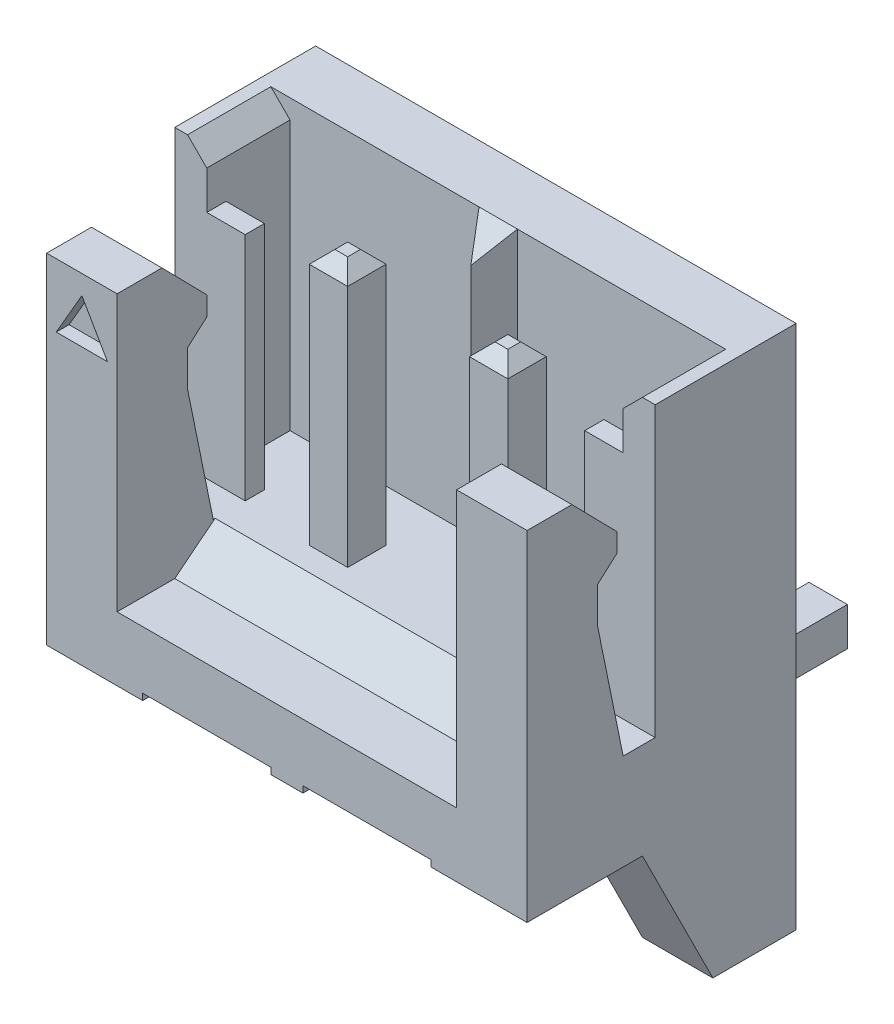
SolidWorks part; units mm, degrees
ref_plane "Спереди" through (0, 0, 0) normal (0, 0, 1) x (1, 0, 0)
ref_plane "Сверху" through (0, 0, 0) normal (0, 1, 0) x (1, 0, 0)
ref_plane "Справа" through (0, 0, 0) normal (1, 0, 0) x (0, 0, -1)
sketch "Эскиз1" plane through (0, 0, 0) normal (0, 1, 0) x (1, 0, 0)
  line L1 (0, 0) -> (7.5, 0)
  line L2 (0, 0) -> (0, -4.2)
  line L3 (0, -4.2) -> (7.5, -4.2)
  line L4 (7.5, 0) -> (7.5, -4.2)
  dimension "D1" = 7.5
  dimension "D2" = 4.2
extrude "Бобышка-Вытянуть1" add sketch "Эскиз1" along normal blind 6
ref_plane "Плоскость1" through (3.75, 0, 0) normal (1, 0, 0) x (0, 0, -1)
sketch "Эскиз2" plane through (0, 6, 0) normal (0, 1, 0) x (1, 0, 0)
  line L0 (0, 0) -> (0, -4.2) construction
  line L1 (0.5, -0.9) -> (7, -0.9)
  line L2 (0.5, -0.9) -> (0.5, -1.9)
  line L3 (1.1, -3.7) -> (6.4, -3.7)
  line L5 (3.75, 0) -> (3.75, -4.2) construction
  line L6 (7.5, 0) -> (0, 0) construction
  line L7 (0, -4.2) -> (7.5, -4.2) construction
  line L9 (0.5, -1.9) -> (1.1, -1.9)
  line L10 (1.1, -1.9) -> (1.1, -3.7)
  line L11 (6.4, -1.9) -> (6.4, -3.7)
  line L12 (7, -1.9) -> (6.4, -1.9)
  line L13 (7, -0.9) -> (7, -1.9)
  line L14 (0.5, -1.9) -> (0.5, -2.2) construction
  line L15 (0.5, -2.2) -> (1.1, -2.2) construction
  point P13 (3.75, -3.3)
  point P14 (3.75, -0.5)
  point P16 (3.75, -3.7)
  point P20 (3.75, -0.9)
  dimension "D1" = 0.5
  dimension "D2" = 0.5
  dimension "D3" = 2.8
  dimension "D4" = 0.3
  dimension "D5" = 0.6
  dimension "D6" = 1.3
extrude "Вырез-Вытянуть1" cut sketch "Эскиз2" against normal blind 5
sketch "Эскиз3" plane through (0, 0, 0) normal (-1, 0, 0) x (0, 0, 1)
  line L0 (2.2, 6) -> (2.2, 1.5)
  line L1 (0, 6) -> (4.2, 6) construction
  line L2 (2.2, 1.5) -> (2.7, 1.5)
  line L3 (2.7, 1.5) -> (3.1, 3.4596)
  line L4 (0, 6) -> (0, 0) construction
  line L5 (4.2, 5.3) -> (3.5, 5.3)
  line L6 (4.2, 6) -> (4.2, 0) construction
  line L8 (3.5, 5.3) -> (2.8, 4.5859)
  line L9 (2.8, 4.5859) -> (2.8, 4.2859)
  line L10 (2.8, 4.2859) -> (3.1, 4.0213)
  line L11 (3.1, 4.0213) -> (3.1, 3.4596)
  line L12 (2.2, 6) -> (4.2, 6)
  line L13 (4.2, 6) -> (4.2, 5.3)
  dimension "D1" = 2.2
  dimension "D2" = 4.5
  dimension "D3" = 0.7
  dimension "D4" = 0.7
  dimension "D5" = 1.4
  dimension "D6" = 1.1
  dimension "D7" = 2
  dimension "D8" = 0.4
  dimension "D9" = 1
  dimension "D10" = 0.3
  dimension "D11" = 0.5
extrude "Вырез-Вытянуть2" cut sketch "Эскиз3" against normal through all
sketch "Эскиз16" plane through (7.5, 0, 0) normal (1, 0, 0) x (0, 0, -1)
  line L0 (-4.2, 5.3) -> (-4.2, 0) construction
  line L1 (-4.2, 0) -> (0, 0) construction
  line L2 (-2.4, 0) -> (-1.3, -2.2)
  line L3 (-1.3, -2.2) -> (0, -2.2)
  line L4 (0, -2.2) -> (0, 0)
  line L5 (-2.4, 0) -> (0, 0)
  dimension "D1" = 2.2
  dimension "D2" = 1.3
  dimension "D3" = 1.8
extrude "Бобышка-Вытянуть6" add sketch "Эскиз16" against normal blind 1.1
mirror "Зеркальное отражение2" about plane through (3.75, 0, 0) normal (1, 0, 0) of "Бобышка-Вытянуть6"
sketch "Эскиз5" plane through (0, 0, 4.2) normal (0, 0, 1) x (1, 0, 0)
  line L0 (7.5, 5.3) -> (0, 5.3) construction
  line L1 (1.1, 5.3) -> (6.4, 5.3)
  line L2 (1.1, 5.3) -> (1.1, 1)
  line L3 (1.1, 1) -> (6.4, 1)
  line L6 (0, 5.3) -> (0, 0) construction
  line L8 (3.75, 1) -> (3.75, 5.3) construction
  line L9 (6.4, 5.3) -> (6.4, 1)
  line L11 (0, 0) -> (7.5, 0) construction
  line L12 (3.75, 0) -> (3.75, 5.3) construction
  line L13 (1.1, 1) -> (6.4, 1) construction
  point P14 (3.75, 3.15)
  dimension "D1" = 1.1
extrude "Вырез-Вытянуть3" cut sketch "Эскиз5" against normal up to next
sketch "Эскиз6" plane through (0.5, 0, 0) normal (1, 0, 0) x (0, 0, -1)
  line L0 (-0.9, 1) -> (-1.9, 1) construction
  line L2 (-3.3, 1) -> (-2.67, 1.5)
  line L3 (-2.67, 1.5) -> (-0.9, 1.5)
  line L4 (-0.9, 1) -> (-0.9, 6) construction
  line L5 (-0.9, 1.5) -> (-0.9, 1)
  line L6 (-0.9, 1) -> (-3.3, 1)
  line L8 (-4.2, 5.3) -> (-4.2, 1) construction
  dimension "D1" = 0.5
  dimension "D2" = 1.77
  dimension "D3" = 0.9
extrude "Бобышка-Вытянуть3" add sketch "Эскиз6" along normal up to next
sketch "Эскиз9" plane through (0, 6, 0) normal (0, 1, 0) x (1, 0, 0)
  line L0 (3.45, -0.9) -> (3.75, -1.3284)
  line L1 (7, -0.9) -> (0.5, -0.9) construction
  line L2 (3.75, -0.9) -> (3.75, -1.3284) construction
  line L3 (7, -0.9) -> (0.5, -0.9) construction
  line L4 (4.05, -0.9) -> (3.75, -1.3284)
  line L5 (3.45, -0.9) -> (4.05, -0.9)
  dimension "D1" = 0.6
  dimension "D2" = 35
  dimension "D3" = 2.95
extrude "Бобышка-Вытянуть5" add sketch "Эскиз9" against normal up to next
sketch "Эскиз11" plane through (0, 0, 0) normal (0, -1, 0) x (1, 0, 0)
  line L0 (0, 4.2) -> (7.5, 4.2) construction
  line L1 (1.5, 4.2) -> (3.5, 4.2)
  line L2 (1.5, 4.2) -> (1.5, 0)
  line L3 (1.5, 0) -> (3.5, 0)
  line L4 (3.5, 4.2) -> (3.5, 0)
  line L5 (2.5, 4.2) -> (2.5, 0) construction
  line L7 (6.4, 0) -> (1.1, 0) construction
  line L9 (2.1, 2.4) -> (2.9, 2.4)
  line L10 (2.1, 2.4) -> (2.1, 1.6)
  line L11 (2.1, 1.6) -> (2.9, 1.6)
  line L12 (2.9, 2.4) -> (2.9, 1.6)
  line L13 (2.1, 2.4) -> (2.9, 1.6) construction
  line L14 (2.1, 1.6) -> (2.9, 2.4) construction
  point P0 (2.5, 2)
  point P8 (2.5, 2)
  dimension "D1" = 2.5
  dimension "D2" = 2
  dimension "D3" = 2
  dimension "D4" = 0.8
extrude "Вырез-Вытянуть5" cut sketch "Эскиз11" against normal blind 0.1
sketch "Эскиз15" plane through (0, 0, 0) normal (0, -1, 0) x (1, 0, 0)
  line L0 (2.1, 2.4) -> (2.9, 1.6) construction
  circle A0 centre (2.5, 2) radius 0.05
  point P4 (2.5, 2)
  dimension "D1" = 0.1
extrude "Вырез-Вытянуть6" cut sketch "Эскиз15" against normal blind 0.1
pattern_linear "Линейный массив2" [suppressed] count 1 spacing 2.5
sketch "Эскиз17" plane through (0, 0, 4.2) normal (0, 0, 1) x (1, 0, 0)
  line L0 (0.55, 5) -> (0.15, 4.3072)
  line L1 (0.15, 4.3072) -> (0.95, 4.3072)
  line L2 (0.95, 4.3072) -> (0.55, 5)
  line L3 (0.55, 5.3) -> (0.55, 0) construction
  line L4 (1.1, 5.3) -> (0, 5.3) construction
  line L5 (0, 0) -> (1.5, 0) construction
  dimension "D1" = 0.8
  dimension "D2" = 0.3
extrude "Вырез-Вытянуть7" cut sketch "Эскиз17" against normal blind 0.2
sketch "Эскиз7" plane through (0, 0, 0) normal (0, -1, 0) x (1, 0, 0)
  line L0 (7.5, 0) -> (0, 0) construction
  line L1 (2.2, 2.3) -> (2.8, 2.3)
  line L2 (2.2, 2.3) -> (2.2, 1.7)
  line L3 (2.2, 1.7) -> (2.8, 1.7)
  line L4 (2.8, 2.3) -> (2.8, 1.7)
  line L5 (2.2, 2.3) -> (2.8, 1.7) construction
  line L6 (2.2, 1.7) -> (2.8, 2.3) construction
  line L7 (0, 2.4) -> (0, 4.2) construction
  point P0 (2.5, 2)
  dimension "D1" = 0.6
  dimension "D2" = 2
  dimension "D3" = 2.5
extrude "Бобышка-Вытянуть4" add sketch "Эскиз7" against normal blind 5.5
sketch "Эскиз18" plane through (0, 0, 0) normal (0, -1, 0) x (1, 0, 0)
  line L1 (2.2, 1.7) -> (2.8, 1.7)
  line L2 (2.2, 1.7) -> (2.2, 2.3)
  line L3 (2.2, 2.3) -> (2.8, 2.3)
  line L4 (2.8, 1.7) -> (2.8, 2.3)
  line L5 (2.2, 1.7) -> (2.8, 2.3) construction
  line L6 (2.2, 2.3) -> (2.8, 1.7) construction
  point P0 (2.5, 2)
sketch3d "Трехмерный эскиз1"
  line L0 (2.5, -0.7, 1.3) -> (2.5, -0.7, -3.2)
  line L1 (2.5, 6, 0) -> (2.5, 0.1, 0) construction
  line L2 (7.5, 6, 0) -> (0, 6, 0) construction
  line L3 (2.5, 0, 2) -> (2.5, -0.7, 2) construction
  line L4 (1.5, 0.1, 0) -> (3.5, 0.1, 0) construction
  line L5 (2.5, -0.7, 1.3) -> (2.5, -0.7, 2) construction
  arc A0 (2.5, 0, 2) -> (2.5, -0.7, 1.3) centre (2.5, 0, 1.3) cw
  point P12 (3.2, 0, 1.3)
  dimension "D1" = 6.7
  dimension "D2" = 3.2
sweep "По траектории1" add profiles "Эскиз18" path "Трехмерный эскиз1"
chamfer "Фаска6" distance 0.2 angle 45 8 edges at (2.5, 5.5, 2.3) (2.2, 5.5, 2) (2.5, 5.5, 1.7) (2.8, 5.5, 2) (2.5, -0.4, -3.2) (2.2, -0.7, -3.2) (2.5, -1, -3.2) (2.8, -0.7, -3.2)
pattern_linear "Линейный массив1" count 2 spacing 2.5 along (1, 0, 0) of "Бобышка-Вытянуть4", "Фаска6", "Вырез-Вытянуть5", "По траектории1"
sketch "Эскиз10" plane through (0.5, 0, 0) normal (1, 0, 0) x (0, 0, -1)
  line L0 (-1.4, 6) -> (-0.9, 6)
  line L1 (-0.9, 6) -> (-1.4, 5.5)
  line L4 (-0.9, 6) -> (-1.9, 6) construction
  line L7 (-2.2, 6) -> (-1.4, 6) construction
  line L8 (-1.4, 5.5) -> (-1.4, 6)
  dimension "D1" = 45
  dimension "D3" = 0.5
  dimension "D4" = 0.8
extrude "Вырез-Вытянуть4" cut sketch "Эскиз10" along normal up to surface (6.5 mm away) contours L1 L8 L0 up to face at (7, 3.75, 1.4)
sketch "Эскиз20" plane through (0, 6, 0) normal (0, 1, 0) x (1, 0, 0)
  line L1 (0.5, -1.9) -> (1.1, -1.9)
  line L2 (0.5, -1.9) -> (0.5, -2.2)
  line L3 (0.5, -2.2) -> (1.1, -2.2)
  line L4 (1.1, -1.9) -> (1.1, -2.2)
extrude "Вырез-Вытянуть9" cut sketch "Эскиз20" against normal blind 0.9
mirror "Зеркальное отражение3" about plane through (3.75, 0, 0) normal (1, 0, 0) of "Вырез-Вытянуть9"
chamfer "Фаска5" distance 0.3 angle 45 2 edges at (7, 6, 1.55) (0.5, 6, 1.55)
sketch "Эскиз19" plane through (0, 0, 0) normal (0, 0, -1) x (-1, 0, 0)
  line L0 (-2.5, -1) -> (-2.5, -0.4) construction
  line L1 (-2.8, -1) -> (-2.2, -1) construction
  line L2 (-2.8, -1) -> (-2.8, -0.4) construction
  line L3 (-2.8, -0.4) -> (-2.2, -0.4) construction
  line L4 (-2.2, -1) -> (-2.2, -0.4) construction
  circle A0 centre (-2.5, -0.7) radius 0.05
  point P8 (-2.5, -0.7)
  dimension "D1" = 0.1
extrude "Вырез-Вытянуть8" cut sketch "Эскиз19" along normal up to surface (3.2 mm away) up to face at (2.5, -0.7, -3.2)
ref_point "Точка1"
equation "\"PINS\" = 2"
equation "\"D1@Линейный массив2\"= \"GUIDE_MASS\""
equation "\"PIN_MASS\"= \"PINS\""
equation "\"D1@Линейный массив1\"=\"PIN_MASS\""
equation "\"GUIDE_MASS\"= \"PINS\" - 1"
equation "\"D1@Эскиз1\"= 5 + ( 2.5 * ( \"PIN_MASS\" - 1 ) )"
